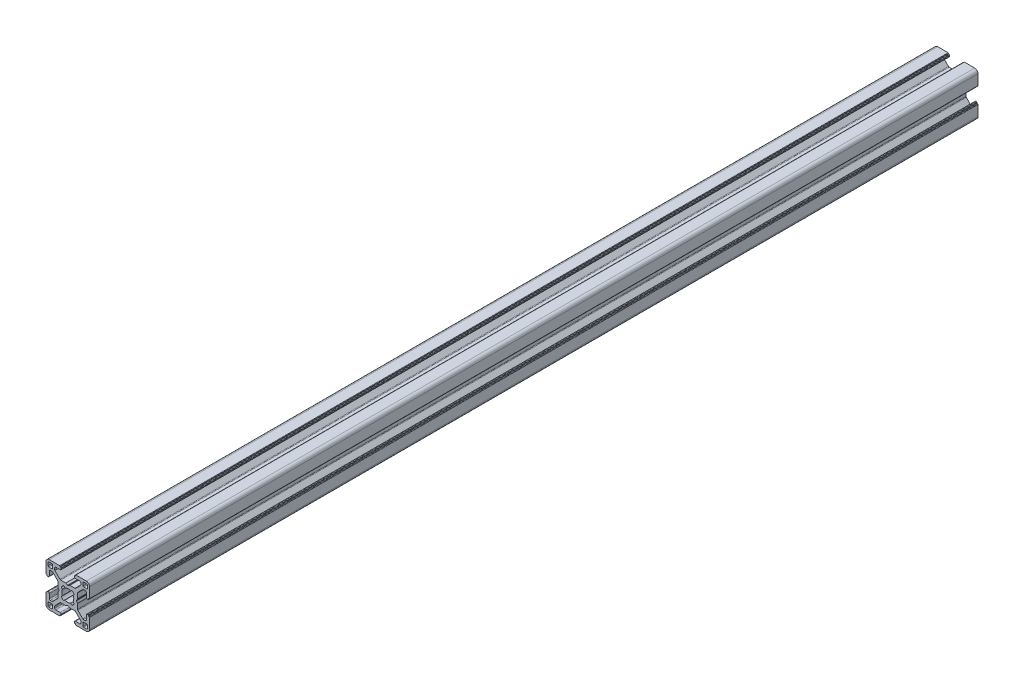
SolidWorks part; units mm, degrees
material "6063-O, Barra estrusa (SS)"
ref_plane "Piano frontale" through (0, 0, 0) normal (0, 0, 1) x (1, 0, 0)
ref_plane "Piano superiore" through (0, 0, 0) normal (0, 1, 0) x (1, 0, 0)
ref_plane "Piano destro" through (0, 0, 0) normal (1, 0, 0) x (0, 0, -1)
ref_plane "Piano1" through (0, 0, 100) normal (0, 0, 1) x (1, 0, 0)
sketch "Schizzo1" plane through (0, 0, 100) normal (0, 0, 1) x (1, 0, 0)
  line L0 (-1.9139, 2.9896) -> (-1.2582, 2.4453)
  line L1 (1.2582, 2.4453) -> (1.9139, 2.9896)
  line L2 (2.9922, 1.9099) -> (2.4453, 1.2582)
  line L3 (2.4453, -1.2582) -> (2.9922, -1.9099)
  line L4 (1.9139, -2.9896) -> (1.2582, -2.4453)
  line L5 (-1.2582, -2.4453) -> (-1.9139, -2.9896)
  line L6 (-2.9922, -1.9099) -> (-2.4453, -1.2582)
  line L7 (-2.4453, 1.2582) -> (-2.9922, 1.9099)
  line L8 (-9.3, 3) -> (-9, 3)
  line L9 (-8.5, 3.5) -> (-8.5, 5.5)
  line L10 (-8, 6) -> (-7.2678, 6)
  line L11 (-6.9142, 5.8536) -> (-4.6464, 3.5858)
  line L12 (-4.5, 3.2322) -> (-4.5, 0.9536)
  line L13 (-4.4732, 0.8536) -> (-4.0381, 0.1)
  line L14 (-4.0381, -0.1) -> (-4.4732, -0.8536)
  line L15 (-4.5, -0.9536) -> (-4.5, -3.2322)
  line L16 (-4.6464, -3.5858) -> (-6.9142, -5.8536)
  line L17 (-7.2678, -6) -> (-8, -6)
  line L18 (-8.5, -5.5) -> (-8.5, -3.5)
  line L19 (-9, -3) -> (-9.3, -3)
  line L20 (-9.5, -3.2) -> (-9.5, -3.35)
  line L21 (-9.7, -3.55) -> (-9.8, -3.55)
  line L22 (-10, -3.75) -> (-10, -8.5)
  line L23 (-8.5, -10) -> (-3.75, -10)
  line L24 (-3.55, -9.8) -> (-3.55, -9.7)
  line L25 (-3.35, -9.5) -> (-3.2, -9.5)
  line L26 (-3, -9.3) -> (-3, -9)
  line L27 (-3.5, -8.5) -> (-5.5, -8.5)
  line L28 (-6, -8) -> (-6, -7.2678)
  line L29 (-5.8536, -6.9142) -> (-3.5858, -4.6464)
  line L30 (-3.2322, -4.5) -> (-0.9536, -4.5)
  line L31 (-0.8536, -4.4732) -> (-0.1, -4.0381)
  line L32 (0.1, -4.0381) -> (0.8536, -4.4732)
  line L33 (0.9536, -4.5) -> (3.2322, -4.5)
  line L34 (3.5858, -4.6464) -> (5.8536, -6.9142)
  line L35 (6, -7.2678) -> (6, -8)
  line L36 (5.5, -8.5) -> (3.5, -8.5)
  line L37 (3, -9) -> (3, -9.3)
  line L38 (3.2, -9.5) -> (3.35, -9.5)
  line L39 (3.55, -9.7) -> (3.55, -9.8)
  line L40 (3.75, -10) -> (8.5, -10)
  line L41 (10, -8.5) -> (10, -3.75)
  line L42 (9.8, -3.55) -> (9.7, -3.55)
  line L43 (9.5, -3.35) -> (9.5, -3.2)
  line L44 (9.3, -3) -> (9, -3)
  line L45 (8.5, -3.5) -> (8.5, -5.5)
  line L46 (8, -6) -> (7.2678, -6)
  line L47 (6.9142, -5.8536) -> (4.6464, -3.5858)
  line L48 (4.5, -3.2322) -> (4.5, -0.9536)
  line L49 (4.4732, -0.8536) -> (4.0381, -0.1)
  line L50 (4.0381, 0.1) -> (4.4732, 0.8536)
  line L51 (4.5, 0.9536) -> (4.5, 3.2322)
  line L52 (4.6464, 3.5858) -> (6.9142, 5.8536)
  line L53 (7.2678, 6) -> (8, 6)
  line L54 (8.5, 5.5) -> (8.5, 3.5)
  line L55 (9, 3) -> (9.3, 3)
  line L56 (9.5, 3.2) -> (9.5, 3.35)
  line L57 (9.7, 3.55) -> (9.8, 3.55)
  line L58 (10, 3.75) -> (10, 8.5)
  line L59 (8.5, 10) -> (3.75, 10)
  line L60 (3.55, 9.8) -> (3.55, 9.7)
  line L61 (3.35, 9.5) -> (3.2, 9.5)
  line L62 (3, 9.3) -> (3, 9)
  line L63 (3.5, 8.5) -> (5.5, 8.5)
  line L64 (6, 8) -> (6, 7.2678)
  line L65 (5.8536, 6.9142) -> (3.5858, 4.6464)
  line L66 (3.2322, 4.5) -> (0.9536, 4.5)
  line L67 (0.8536, 4.4732) -> (0.1, 4.0381)
  line L68 (-0.1, 4.0381) -> (-0.8536, 4.4732)
  line L69 (-0.9536, 4.5) -> (-3.2322, 4.5)
  line L70 (-3.5858, 4.6464) -> (-5.8536, 6.9142)
  line L71 (-6, 7.2678) -> (-6, 8)
  line L72 (-5.5, 8.5) -> (-3.5, 8.5)
  line L73 (-3, 9) -> (-3, 9.3)
  line L74 (-3.2, 9.5) -> (-3.35, 9.5)
  line L75 (-3.55, 9.7) -> (-3.55, 9.8)
  line L76 (-3.75, 10) -> (-8.5, 10)
  line L77 (-10, 8.5) -> (-10, 3.75)
  line L78 (-9.8, 3.55) -> (-9.7, 3.55)
  line L79 (-9.5, 3.35) -> (-9.5, 3.2)
  line L80 (8.7, 7) -> (7.3, 7)
  line L81 (-7.3, 7) -> (-8.7, 7)
  line L82 (-7, 7.3) -> (-7, 8.7)
  line L83 (-7.3, 9) -> (-8.7, 9)
  line L84 (-9, 7.3) -> (-9, 8.7)
  line L85 (9, 7.3) -> (9, 8.7)
  line L86 (8.7, 9) -> (7.3, 9)
  line L87 (7, 7.3) -> (7, 8.7)
  line L88 (8.7, -9) -> (7.3, -9)
  line L89 (9, -8.7) -> (9, -7.3)
  line L90 (8.7, -7) -> (7.3, -7)
  line L91 (7, -8.7) -> (7, -7.3)
  line L92 (-7.3, -9) -> (-8.7, -9)
  line L93 (-7, -8.7) -> (-7, -7.3)
  line L94 (-7.3, -7) -> (-8.7, -7)
  line L95 (-9, -8.7) -> (-9, -7.3)
  arc A0 (-1.2582, 2.4453) -> (1.2582, 2.4453) centre (0, 0) cw
  arc A1 (1.9139, 2.9896) -> (2.9922, 1.9099) centre (0, 0) cw
  arc A2 (2.4453, 1.2582) -> (2.4453, -1.2582) centre (0, 0) cw
  arc A3 (2.9922, -1.9099) -> (1.9139, -2.9896) centre (0, 0) cw
  arc A4 (1.2582, -2.4453) -> (-1.2582, -2.4453) centre (0, 0) cw
  arc A5 (-1.9139, -2.9896) -> (-2.9922, -1.9099) centre (0, 0) cw
  arc A6 (-2.4453, -1.2582) -> (-2.4453, 1.2582) centre (0, 0) cw
  arc A7 (-2.9922, 1.9099) -> (-1.9139, 2.9896) centre (0, 0) cw
  arc A8 (-9.5, 3.2) -> (-9.3, 3) centre (-9.3, 3.2) ccw
  arc A9 (-9, 3) -> (-8.5, 3.5) centre (-9, 3.5) ccw
  arc A10 (-8.5, 5.5) -> (-8, 6) centre (-8, 5.5) cw
  arc A11 (-7.2678, 6) -> (-6.9142, 5.8536) centre (-7.2678, 5.5) cw
  arc A12 (-4.6464, 3.5858) -> (-4.5, 3.2322) centre (-5, 3.2322) cw
  arc A13 (-4.5, 0.9536) -> (-4.4732, 0.8536) centre (-4.3, 0.9536) ccw
  arc A14 (-4.0381, 0.1) -> (-4.0381, -0.1) centre (-4.2113, 0) cw
  arc A15 (-4.4732, -0.8536) -> (-4.5, -0.9536) centre (-4.3, -0.9536) ccw
  arc A16 (-4.5, -3.2322) -> (-4.6464, -3.5858) centre (-5, -3.2322) cw
  arc A17 (-6.9142, -5.8536) -> (-7.2678, -6) centre (-7.2678, -5.5) cw
  arc A18 (-8, -6) -> (-8.5, -5.5) centre (-8, -5.5) cw
  arc A19 (-8.5, -3.5) -> (-9, -3) centre (-9, -3.5) ccw
  arc A20 (-9.3, -3) -> (-9.5, -3.2) centre (-9.3, -3.2) ccw
  arc A21 (-9.5, -3.35) -> (-9.7, -3.55) centre (-9.7, -3.35) cw
  arc A22 (-9.8, -3.55) -> (-10, -3.75) centre (-9.8, -3.75) ccw
  arc A23 (-10, -8.5) -> (-8.5, -10) centre (-8.5, -8.5) ccw
  arc A24 (-3.75, -10) -> (-3.55, -9.8) centre (-3.75, -9.8) ccw
  arc A25 (-3.55, -9.7) -> (-3.35, -9.5) centre (-3.35, -9.7) cw
  arc A26 (-3.2, -9.5) -> (-3, -9.3) centre (-3.2, -9.3) ccw
  arc A27 (-3, -9) -> (-3.5, -8.5) centre (-3.5, -9) ccw
  arc A28 (-5.5, -8.5) -> (-6, -8) centre (-5.5, -8) cw
  arc A29 (-6, -7.2678) -> (-5.8536, -6.9142) centre (-5.5, -7.2678) cw
  arc A30 (-3.5858, -4.6464) -> (-3.2322, -4.5) centre (-3.2322, -5) cw
  arc A31 (-0.9536, -4.5) -> (-0.8536, -4.4732) centre (-0.9536, -4.3) ccw
  arc A32 (-0.1, -4.0381) -> (0.1, -4.0381) centre (0, -4.2113) cw
  arc A33 (0.8536, -4.4732) -> (0.9536, -4.5) centre (0.9536, -4.3) ccw
  arc A34 (3.2322, -4.5) -> (3.5858, -4.6464) centre (3.2322, -5) cw
  arc A35 (5.8536, -6.9142) -> (6, -7.2678) centre (5.5, -7.2678) cw
  arc A36 (6, -8) -> (5.5, -8.5) centre (5.5, -8) cw
  arc A37 (3.5, -8.5) -> (3, -9) centre (3.5, -9) ccw
  arc A38 (3, -9.3) -> (3.2, -9.5) centre (3.2, -9.3) ccw
  arc A39 (3.35, -9.5) -> (3.55, -9.7) centre (3.35, -9.7) cw
  arc A40 (3.55, -9.8) -> (3.75, -10) centre (3.75, -9.8) ccw
  arc A41 (8.5, -10) -> (10, -8.5) centre (8.5, -8.5) ccw
  arc A42 (10, -3.75) -> (9.8, -3.55) centre (9.8, -3.75) ccw
  arc A43 (9.7, -3.55) -> (9.5, -3.35) centre (9.7, -3.35) cw
  arc A44 (9.5, -3.2) -> (9.3, -3) centre (9.3, -3.2) ccw
  arc A45 (9, -3) -> (8.5, -3.5) centre (9, -3.5) ccw
  arc A46 (8.5, -5.5) -> (8, -6) centre (8, -5.5) cw
  arc A47 (7.2678, -6) -> (6.9142, -5.8536) centre (7.2678, -5.5) cw
  arc A48 (4.6464, -3.5858) -> (4.5, -3.2322) centre (5, -3.2322) cw
  arc A49 (4.5, -0.9536) -> (4.4732, -0.8536) centre (4.3, -0.9536) ccw
  arc A50 (4.0381, -0.1) -> (4.0381, 0.1) centre (4.2113, 0) cw
  arc A51 (4.4732, 0.8536) -> (4.5, 0.9536) centre (4.3, 0.9536) ccw
  arc A52 (4.5, 3.2322) -> (4.6464, 3.5858) centre (5, 3.2322) cw
  arc A53 (6.9142, 5.8536) -> (7.2678, 6) centre (7.2678, 5.5) cw
  arc A54 (8, 6) -> (8.5, 5.5) centre (8, 5.5) cw
  arc A55 (8.5, 3.5) -> (9, 3) centre (9, 3.5) ccw
  arc A56 (9.3, 3) -> (9.5, 3.2) centre (9.3, 3.2) ccw
  arc A57 (9.5, 3.35) -> (9.7, 3.55) centre (9.7, 3.35) cw
  arc A58 (9.8, 3.55) -> (10, 3.75) centre (9.8, 3.75) ccw
  arc A59 (10, 8.5) -> (8.5, 10) centre (8.5, 8.5) ccw
  arc A60 (3.75, 10) -> (3.55, 9.8) centre (3.75, 9.8) ccw
  arc A61 (3.55, 9.7) -> (3.35, 9.5) centre (3.35, 9.7) cw
  arc A62 (3.2, 9.5) -> (3, 9.3) centre (3.2, 9.3) ccw
  arc A63 (3, 9) -> (3.5, 8.5) centre (3.5, 9) ccw
  arc A64 (5.5, 8.5) -> (6, 8) centre (5.5, 8) cw
  arc A65 (6, 7.2678) -> (5.8536, 6.9142) centre (5.5, 7.2678) cw
  arc A66 (3.5858, 4.6464) -> (3.2322, 4.5) centre (3.2322, 5) cw
  arc A67 (0.9536, 4.5) -> (0.8536, 4.4732) centre (0.9536, 4.3) ccw
  arc A68 (0.1, 4.0381) -> (-0.1, 4.0381) centre (0, 4.2113) cw
  arc A69 (-0.8536, 4.4732) -> (-0.9536, 4.5) centre (-0.9536, 4.3) ccw
  arc A70 (-3.2322, 4.5) -> (-3.5858, 4.6464) centre (-3.2322, 5) cw
  arc A71 (-5.8536, 6.9142) -> (-6, 7.2678) centre (-5.5, 7.2678) cw
  arc A72 (-6, 8) -> (-5.5, 8.5) centre (-5.5, 8) cw
  arc A73 (-3.5, 8.5) -> (-3, 9) centre (-3.5, 9) ccw
  arc A74 (-3, 9.3) -> (-3.2, 9.5) centre (-3.2, 9.3) ccw
  arc A75 (-3.35, 9.5) -> (-3.55, 9.7) centre (-3.35, 9.7) cw
  arc A76 (-3.55, 9.8) -> (-3.75, 10) centre (-3.75, 9.8) ccw
  arc A77 (-8.5, 10) -> (-10, 8.5) centre (-8.5, 8.5) ccw
  arc A78 (-10, 3.75) -> (-9.8, 3.55) centre (-9.8, 3.75) ccw
  arc A79 (-9.7, 3.55) -> (-9.5, 3.35) centre (-9.7, 3.35) cw
  arc A80 (-8.7, 7) -> (-9, 7.3) centre (-8.7, 7.3) cw
  arc A81 (-7, 8.7) -> (-7.3, 9) centre (-7.3, 8.7) ccw
  arc A82 (-7.3, 7) -> (-7, 7.3) centre (-7.3, 7.3) ccw
  arc A83 (-8.7, 9) -> (-9, 8.7) centre (-8.7, 8.7) ccw
  arc A84 (7.3, 7) -> (7, 7.3) centre (7.3, 7.3) cw
  arc A85 (9, 8.7) -> (8.7, 9) centre (8.7, 8.7) ccw
  arc A86 (8.7, 7) -> (9, 7.3) centre (8.7, 7.3) ccw
  arc A87 (7.3, 9) -> (7, 8.7) centre (7.3, 8.7) ccw
  arc A88 (7.3, -9) -> (7, -8.7) centre (7.3, -8.7) cw
  arc A89 (9, -7.3) -> (8.7, -7) centre (8.7, -7.3) ccw
  arc A90 (8.7, -9) -> (9, -8.7) centre (8.7, -8.7) ccw
  arc A91 (7.3, -7) -> (7, -7.3) centre (7.3, -7.3) ccw
  arc A92 (-8.7, -9) -> (-9, -8.7) centre (-8.7, -8.7) cw
  arc A93 (-7, -7.3) -> (-7.3, -7) centre (-7.3, -7.3) ccw
  arc A94 (-7.3, -9) -> (-7, -8.7) centre (-7.3, -8.7) ccw
  arc A95 (-8.7, -7) -> (-9, -7.3) centre (-8.7, -7.3) ccw
  dimension "D1" = 0.3
  dimension "D2" = 1
  dimension "D3" = 1
  dimension "D4" = 1
  dimension "D7" = 1
  dimension "D8" = 1
  dimension "D9" = 1
  dimension "D10" = 1
  dimension "D5" = 2
  dimension "D6" = 2
extrude "Estrusione-Estrusione1" add sketch "Schizzo1" against normal blind 408
